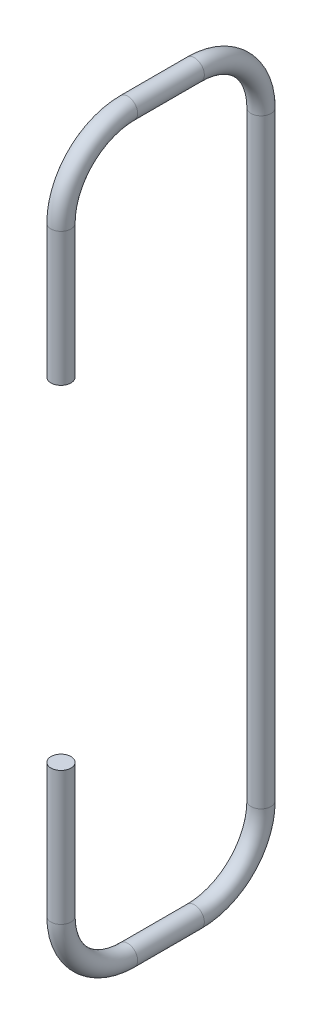
SolidWorks part; units mm, degrees
material "Сталь 3 ГОСТ 535-88"
ref_plane "Спереди" through (0, 0, 0) normal (0, 0, 1) x (1, 0, 0)
ref_plane "Сверху" through (0, 0, 0) normal (0, 1, 0) x (1, 0, 0)
ref_plane "Справа" through (0, 0, 0) normal (1, 0, 0) x (0, 0, -1)
sketch "Эскиз1" plane through (0, 0, 0) normal (1, 0, 0) x (0, 0, -1)
  line L0 (0, 45) -> (0, 0)
  line L1 (-30, 25) -> (-30, 45)
  line L2 (-20, 55) -> (-10, 55)
  line L3 (-10, 45) -> (-2.9289, 52.0711) construction
  line L4 (0, 30) -> (-10.5616, 30) construction
  arc A0 (0, 45) -> (-10, 55) centre (-10, 45) ccw
  arc A1 (-30, 45) -> (-20, 55) centre (-20, 45) cw
  point P8 (0, 55)
  point P11 (-30, 55)
  dimension "D4" = 10
  dimension "D1" = 30
  dimension "D2" = 30
  dimension "D3" = 55
  dimension "D5" = 30
sketch "Эскиз2" plane through (0, 0, 0) normal (0, 1, 0) x (1, 0, 0)
  circle A0 centre (0, 0) radius 1.5
  dimension "D1" = 3
sweep "По траектории1" add profiles "Эскиз2" path "Эскиз1"
mirror "Зеркальное отражение1" about plane through (0, 0, 0) normal (0, 1, 0) of bodies 103
